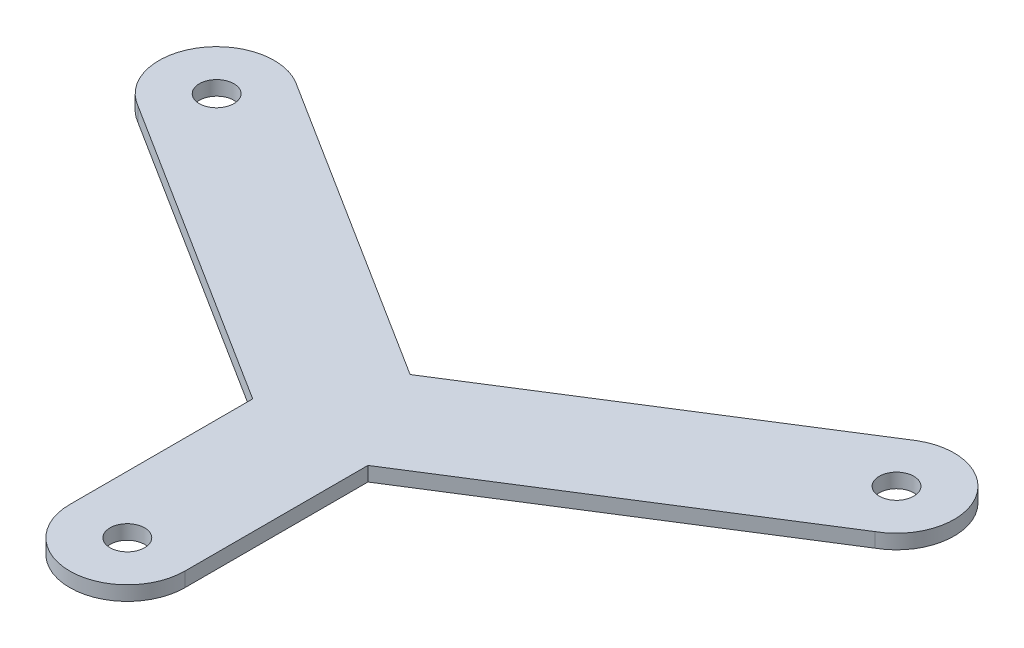
SolidWorks part; units mm, degrees
ref_plane "Front Plane" through (0, 0, 0) normal (0, 0, 1) x (1, 0, 0)
ref_plane "Top Plane" through (0, 0, 0) normal (0, 1, 0) x (1, 0, 0)
ref_plane "Right Plane" through (0, 0, 0) normal (1, 0, 0) x (0, 0, -1)
sketch "Sketch1" plane through (0, 0, 0) normal (0, 1, 0) x (1, 0, 0)
  line L0 (0, -74.5) -> (0, 74.5) construction
  line L1 (-118, 74.5) -> (118, 74.5) construction
  line L2 (-118, 74.5) -> (0, 0) construction
  line L3 (-107.8926, 91.758) -> (0, 23.6526)
  line L4 (-127.8925, 57.1179) -> (-20, -10.9876)
  line L5 (118, 74.5) -> (0, 0) construction
  line L6 (127.8925, 57.1179) -> (20, -10.9876)
  line L7 (107.8926, 91.758) -> (0, 23.6526)
  line L8 (0, 0) -> (0, -74.5) construction
  line L9 (20, -10.9876) -> (20, -74.4729)
  line L10 (-20, -10.9876) -> (-20, -74.4729)
  line L11 (20, -10.9876) -> (0, 23.6526) construction
  line L12 (-20, -10.9876) -> (0, 23.6526) construction
  line L13 (20, -10.9876) -> (-20, -10.9876) construction
  arc A0 (-107.8926, 91.758) -> (-127.8925, 57.1179) centre (-118, 74.5) ccw
  arc A2 (127.8925, 57.1179) -> (107.8926, 91.758) centre (118, 74.5) ccw
  arc A5 (-20, -74.4729) -> (20, -74.4729) centre (0, -74.5) ccw
  point P5 (-59, 37.25)
  point P11 (59, 37.25)
  point P17 (0, -10.9876)
  dimension "D3" = 20
  dimension "D1" = 236
  dimension "D2" = 149
  dimension "D4" = 50.8474
extrude "Extrude1" add sketch "Sketch1" along normal blind 5
sketch "Sketch2" plane through (0, 5, 0) normal (0, 1, 0) x (-1, 0, 0)
  circle A0 centre (118, -74.5) radius 6
  circle A1 centre (-118, -74.5) radius 6
  circle A2 centre (0, 74.5) radius 6
  dimension "D1" = 12
extrude "Extrude2" cut sketch "Sketch2" against normal up to next
